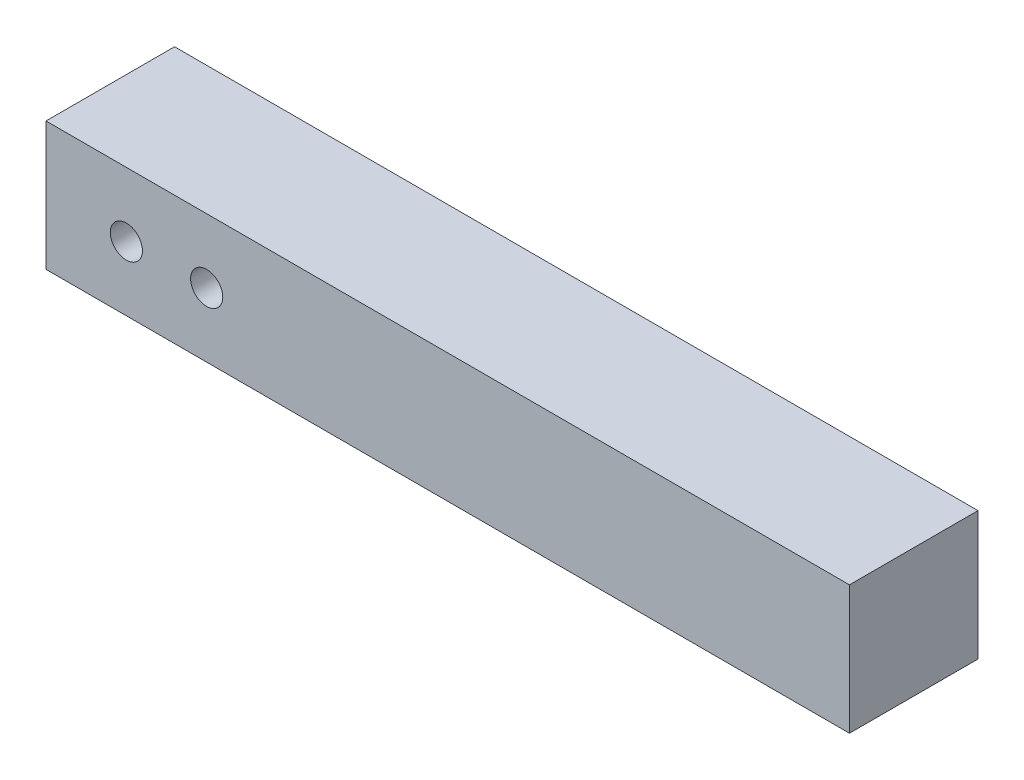
SolidWorks part; units mm, degrees
material "AISI 1020"
ref_plane "Front Plane" through (0, 0, 0) normal (0, 0, 1) x (1, 0, 0)
ref_plane "Top Plane" through (0, 0, 0) normal (0, 1, 0) x (1, 0, 0)
ref_plane "Right Plane" through (0, 0, 0) normal (1, 0, 0) x (0, 0, -1)
other "Configuration Table"
sketch "Sketch1" plane through (0, 0, 0) normal (0, 0, 1) x (1, 0, 0)
  line L1 (0, 0) -> (250, 0)
  line L2 (0, 0) -> (0, -40)
  line L3 (0, -40) -> (250, -40)
  line L4 (250, 0) -> (250, -40)
  circle A0 centre (25, -20) radius 5
  circle A1 centre (50, -20) radius 5
  dimension "D3" = 10
  dimension "D4" = 10
  dimension "D1" = 40
  dimension "D2" = 250
  dimension "D5" = 25
  dimension "D6" = 25
  dimension "D7" = 20
extrude "Boss-Extrude1" add sketch "Sketch1" along normal blind 40
